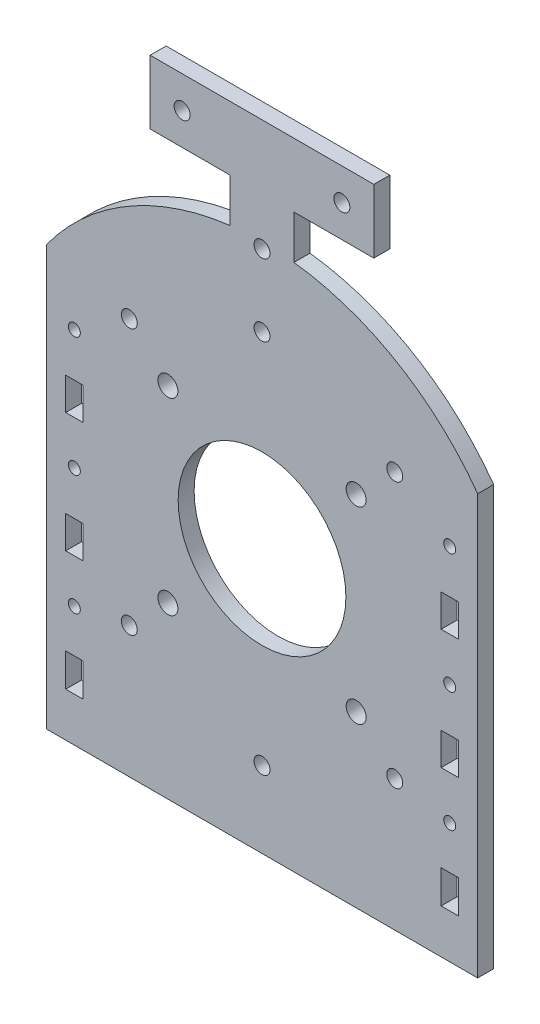
SolidWorks part; units mm, degrees
ref_plane "前视基准面" through (0, 0, 0) normal (0, 0, 1) x (1, 0, 0)
ref_plane "上视基准面" through (0, 0, 0) normal (0, 1, 0) x (1, 0, 0)
ref_plane "右视基准面" through (0, 0, 0) normal (1, 0, 0) x (0, 0, -1)
sketch "草图1" plane through (0, 0, 0) normal (0, 0, 1) x (1, 0, 0)
  line L0 (-47, 39) -> (-47, 36)
  line L1 (-47, 26.5) -> (-47, 18.5) construction
  line L3 (-49.15, 18.45) -> (-44.85, 18.45)
  line L4 (-49.15, 18.45) -> (-49.15, 26.55)
  line L5 (-49.15, 26.55) -> (-44.85, 26.55)
  line L6 (-44.85, 18.45) -> (-44.85, 26.55)
  line L7 (-49.15, 18.45) -> (-44.85, 26.55) construction
  line L8 (-49.15, 26.55) -> (-44.85, 18.45) construction
  line L20 (-44.85, -11.55) -> (-44.85, -3.45)
  line L21 (-49.15, -11.55) -> (-44.85, -11.55)
  line L22 (-49.15, -11.55) -> (-49.15, -3.45)
  line L23 (-49.15, -3.45) -> (-44.85, -3.45)
  line L24 (-44.85, -41.55) -> (-44.85, -33.25)
  line L25 (-49.15, -41.55) -> (-44.85, -41.55)
  line L26 (-49.15, -41.55) -> (-49.15, -33.25)
  line L27 (-49.15, -33.25) -> (-44.85, -33.25)
  line L29 (-54, 52.4) -> (-54, -52.6)
  line L32 (0, 71) -> (0, -44) construction
  line L33 (-23.57, 37.07) -> (-23.57, -10.07) construction
  line L34 (23.57, 37.07) -> (23.57, -10.07) construction
  line L35 (49.15, 26.55) -> (44.85, 18.45) construction
  line L36 (49.15, 18.45) -> (44.85, 26.55) construction
  line L37 (47, 26.5) -> (47, 18.5) construction
  line L38 (54, 52.4) -> (54, -52.6)
  line L39 (49.15, -33.25) -> (44.85, -33.25)
  line L40 (49.15, -41.55) -> (49.15, -33.25)
  line L41 (49.15, -41.55) -> (44.85, -41.55)
  line L42 (44.85, -41.55) -> (44.85, -33.25)
  line L43 (49.15, -3.45) -> (44.85, -3.45)
  line L44 (49.15, -11.55) -> (49.15, -3.45)
  line L45 (49.15, -11.55) -> (44.85, -11.55)
  line L46 (44.85, -11.55) -> (44.85, -3.45)
  line L47 (44.85, 18.45) -> (44.85, 26.55)
  line L48 (49.15, 26.55) -> (44.85, 26.55)
  line L49 (49.15, 18.45) -> (49.15, 26.55)
  line L50 (49.15, 18.45) -> (44.85, 18.45)
  line L51 (47, 39) -> (47, 36)
  line L52 (-54, 52.4) -> (54, 52.4) construction
  line L53 (54, -52.6) -> (-54, -52.6)
  line L54 (-47, 7.5) -> (-54, 7.5) construction
  line L55 (-47, 37.5) -> (-47, 22.5) construction
  line L56 (-47, 22.5) -> (-47, 7.5) construction
  line L57 (-47, 7.5) -> (-47, -22.5) construction
  line L58 (-49.15, 18.45) -> (-49.15, -3.45) construction
  line L59 (-49.15, -11.55) -> (-49.15, -33.25)
  line L60 (0, 78.5) -> (0, 84.5) construction
  line L61 (-28, 106.5) -> (28, 106.5)
  line L62 (28, 106.5) -> (28, 90.5)
  line L63 (28, 90.5) -> (8, 90.5)
  line L64 (8, 90.5) -> (8, 79.5697)
  line L65 (-28, 106.5) -> (-28, 90.5)
  line L66 (-28, 90.5) -> (-8, 90.5)
  line L67 (-8, 90.5) -> (-8, 79.5697)
  circle A0 centre (-47, 37.5) radius 1.5
  circle A4 centre (-47, 7.5) radius 1.5
  circle A5 centre (-47, -22.5) radius 1.5
  circle A7 centre (-23.57, 37.07) radius 2.5
  circle A10 centre (-23.57, -10.07) radius 2.5
  circle A11 centre (23.57, -10.07) radius 2.5
  circle A12 centre (23.57, 37.07) radius 2.5
  circle A13 centre (47, -22.5) radius 1.5
  circle A14 centre (47, 7.5) radius 1.5
  circle A15 centre (47, 37.5) radius 1.5
  circle A16 centre (0, 13.5) radius 21
  circle A17 centre (0, 13.5) radius 47 construction
  circle A18 centre (0, 60.5) radius 2
  arc A40 (-54, 52.4) -> (54, 52.4) centre (0, 13.5) cw construction
  circle A41 centre (33.234, 46.734) radius 2
  circle A42 centre (47, 13.5) radius 2 construction
  circle A43 centre (33.234, -19.734) radius 2
  circle A44 centre (0, -33.5) radius 2
  circle A45 centre (-33.234, -19.734) radius 2
  circle A46 centre (-47, 13.5) radius 2 construction
  circle A47 centre (-33.234, 46.734) radius 2
  circle A48 centre (0, 78.5) radius 2
  circle A50 centre (-20, 98.5) radius 2
  circle A51 centre (20, 98.5) radius 2
  arc A52 (-54, 52.4) -> (-8, 79.5697) centre (0, 13.5) cw
  arc A53 (8, 79.5697) -> (54, 52.4) centre (0, 13.5) cw
  point P6 (-47, 22.5)
  point P59 (47, 22.5)
  dimension "D3" = 5
  dimension "D6" = 23.57
  dimension "D8" = 15
  dimension "D10" = 65
  dimension "D11" = 94
  dimension "D14" = 30
  dimension "D16" = 4
  dimension "D1" = 8.1
  dimension "D2" = 4.3
  dimension "D4" = 4.85
  dimension "D5" = 8
  dimension "D7" = 47.14
  dimension "D9" = 30
  dimension "D12" = 24
  dimension "D13" = 15
  dimension "D15" = 30
  dimension "D17" = 20
  dimension "D18" = 20
  dimension "D19" = 20
  dimension "D20" = 20
  dimension "D21" = 8
  dimension "D22" = 8
  dimension "D23" = 8
  dimension "D24" = 8
  dimension "D25" = 8
  dimension "D26" = 8
extrude "凸台-拉伸1" add sketch "草图1" along normal blind 4
